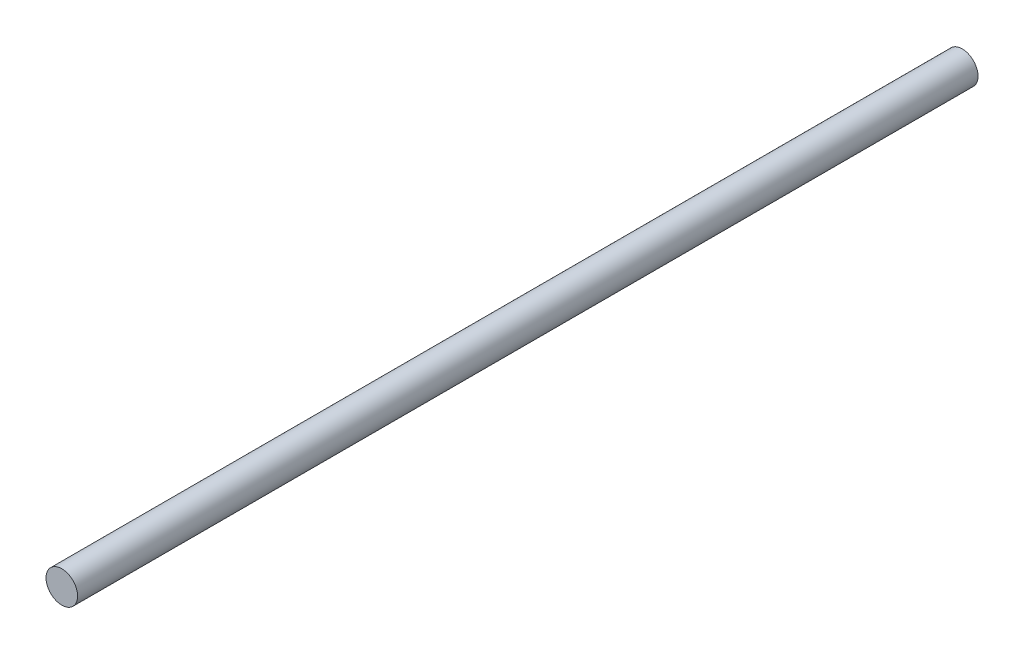
SolidWorks part; units mm, degrees
material "AISI 304"
ref_plane "Alzado" through (0, 0, 0) normal (0, 0, 1) x (1, 0, 0)
ref_plane "Planta" through (0, 0, 0) normal (0, 1, 0) x (1, 0, 0)
ref_plane "Vista lateral" through (0, 0, 0) normal (1, 0, 0) x (0, 0, -1)
sketch "Sk_Varilla" plane through (0, 0, 0) normal (0, 0, 1) x (1, 0, 0)
  circle A0 centre (0, 0) radius 2
  dimension "D1" = 4
extrude "Varilla" add sketch "Sk_Varilla" along normal blind 114 from offset 57
